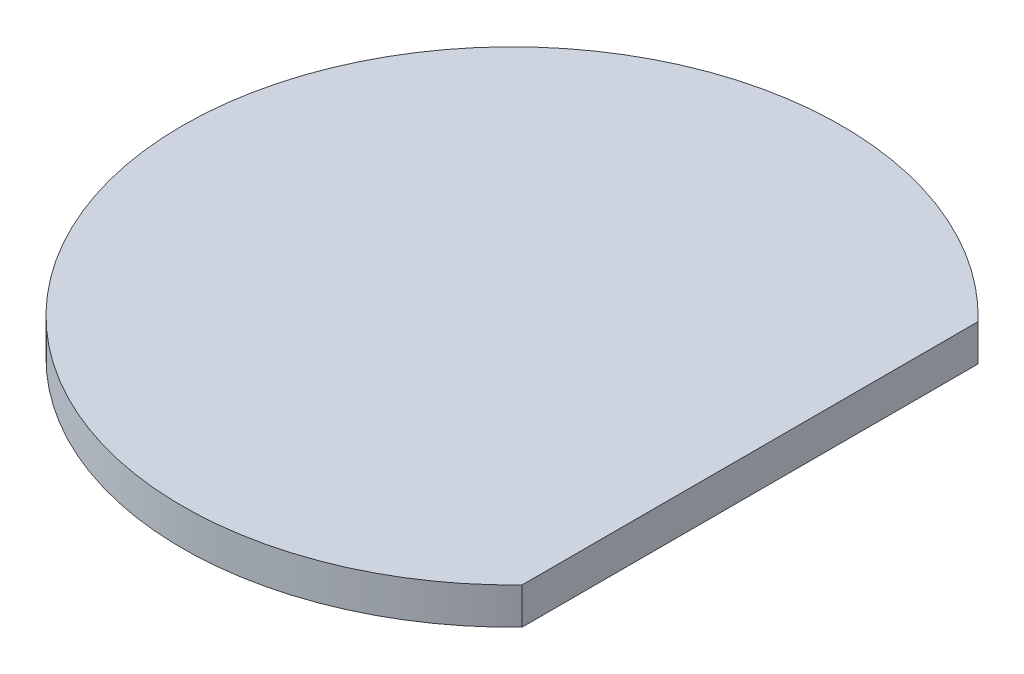
SolidWorks part; units mm, degrees
material "OMD-98"
ref_plane "Front Plane" through (0, 0, 0) normal (0, 0, 1) x (1, 0, 0)
ref_plane "Top Plane" through (0, 0, 0) normal (0, 1, 0) x (1, 0, 0)
ref_plane "Right Plane" through (0, 0, 0) normal (1, 0, 0) x (0, 0, -1)
sketch "Sketch1" plane through (0, 0, 0) normal (0, 1, 0) x (1, 0, 0)
  line L0 (6.5, 6.2249) -> (6.5, -6.2249)
  circle A0 centre (0, 0) radius 9
  dimension "D1" = 18
  dimension "D2" = 6.5
extrude "Boss-Extrude1" add sketch "Sketch1" along normal blind 1 contours L0 A0
